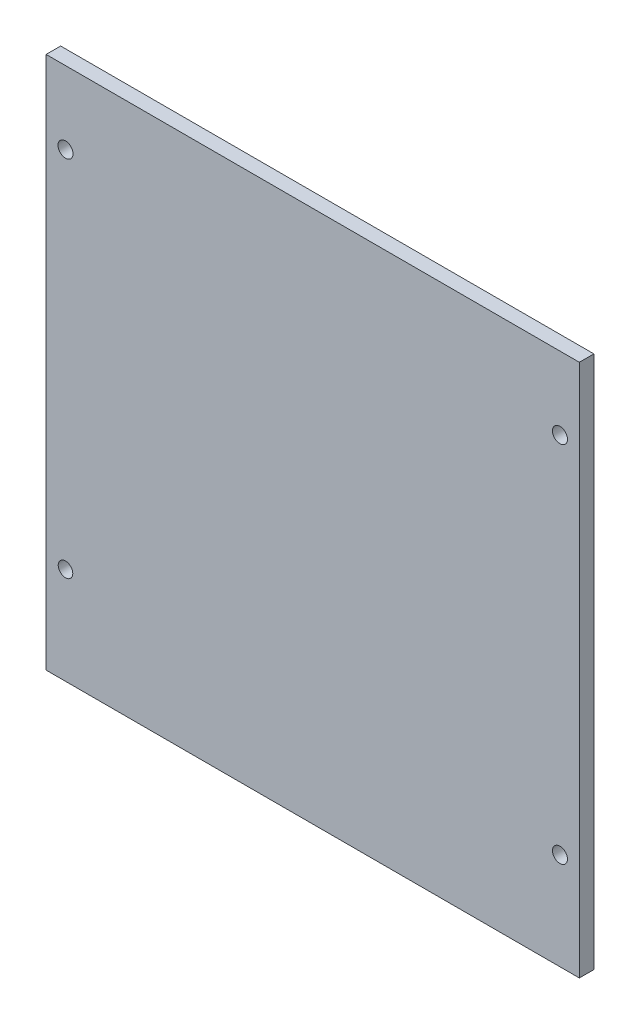
SolidWorks part; units mm, degrees
ref_plane "前视基准面" through (0, 0, 0) normal (0, 0, 1) x (1, 0, 0)
ref_plane "上视基准面" through (0, 0, 0) normal (0, 1, 0) x (1, 0, 0)
ref_plane "右视基准面" through (0, 0, 0) normal (1, 0, 0) x (0, 0, -1)
other "Configuration Table"
sketch "草图1" plane through (0, 0, 0) normal (0, 0, 1) x (1, 0, 0)
  line L1 (55, -55) -> (-55, -55)
  line L2 (55, -55) -> (55, 55)
  line L3 (55, 55) -> (-55, 55)
  line L4 (-55, -55) -> (-55, 55)
  line L5 (55, -55) -> (-55, 55) construction
  line L6 (55, 55) -> (-55, -55) construction
  point P0 (0, 0)
  dimension "D1" = 110
  dimension "D2" = 110
extrude "凸台-拉伸1" add sketch "草图1" along normal blind 3
sketch "草图2" plane through (0, 0, 3) normal (0, 0, 1) x (1, 0, 0)
  circle A0 centre (51, 40) radius 1.55
  circle A1 centre (51, -35) radius 1.55
  circle A2 centre (-51, 40) radius 1.55
  circle A3 centre (-51, -35) radius 1.5
extrude "切除-拉伸1" cut sketch "草图2" against normal blind 10
